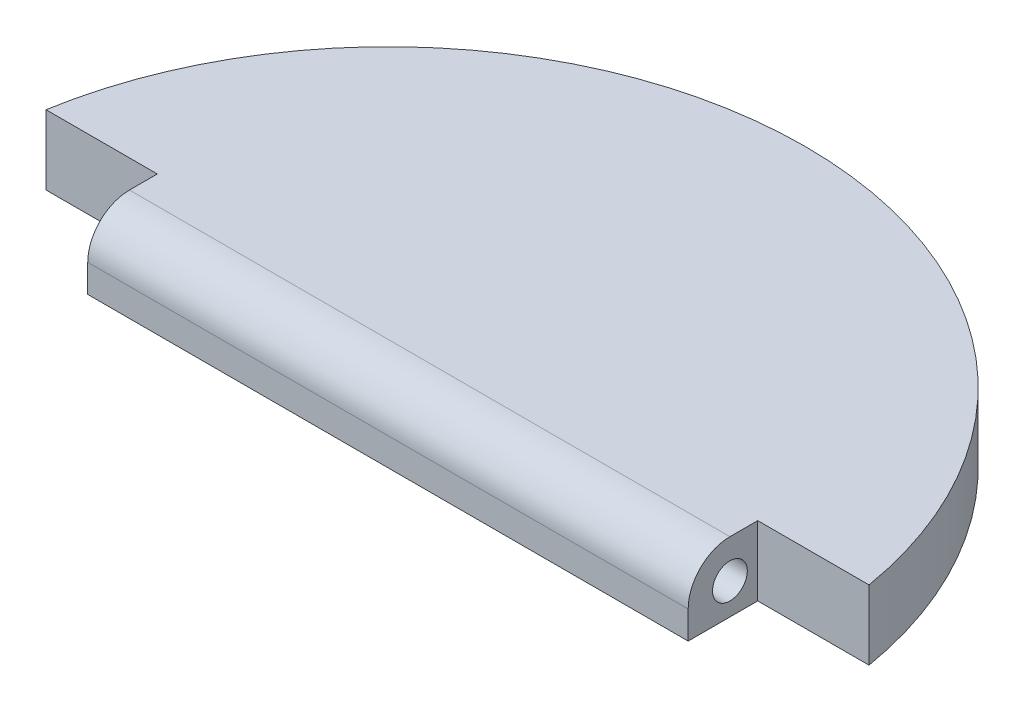
SolidWorks part; units mm, degrees
ref_plane "Front Plane" through (0, 0, 0) normal (0, 0, 1) x (1, 0, 0)
ref_plane "Top Plane" through (0, 0, 0) normal (0, 1, 0) x (1, 0, 0)
ref_plane "Right Plane" through (0, 0, 0) normal (1, 0, 0) x (0, 0, -1)
sketch "Sketch1" plane through (0, 0, 0) normal (0, 1, 0) x (1, 0, 0)
  line L0 (-30, 0) -> (30, 0)
  arc A0 (30, 0) -> (-30, 0) centre (0, 0) ccw
  dimension "D1" = 60
extrude "Boss-Extrude1" add sketch "Sketch1" along normal blind 5
sketch "Sketch5" plane through (0, 5, 0) normal (0, 1, 0) x (1, 0, 0)
  line L0 (-21.5804, 0) -> (-21.5804, 5)
  line L1 (-30, 0) -> (30, 0) construction
  line L2 (-21.5804, 5) -> (-29.5804, 5)
  line L3 (-30, 0) -> (-21.5804, 0)
  line L4 (0, -4.411) -> (0, 4.411) construction
  line L5 (21.5804, 5) -> (29.5804, 5)
  line L6 (21.5804, 0) -> (21.5804, 5)
  line L7 (30, 0) -> (21.5804, 0)
  arc A0 (30, 0) -> (-30, 0) centre (0, 0) ccw construction
  arc A1 (-29.5804, 5) -> (-30, 0) centre (0, 0) ccw
  arc A2 (29.5804, 5) -> (30, 0) centre (0, 0) cw
  dimension "D1" = 8
  dimension "D2" = 5
extrude "Cut-Extrude1" cut sketch "Sketch5" against normal blind 10
fillet "Fillet2" radius 3 1 edges at (0, 5, 0)
sketch "Sketch6" plane through (21.5804, 0, 0) normal (1, 0, 0) x (0, 0, -1)
  line L0 (5, 0) -> (0, 0) construction
  line L1 (0, 0) -> (0, 2) construction
  circle A0 centre (3, 2.25) radius 1.25
  dimension "D1" = 2.5
  dimension "D2" = 2.25
  dimension "D3" = 3
extrude "Cut-Extrude2" cut sketch "Sketch6" against normal blind 3
sketch "Sketch7" plane through (-21.5804, 0, 0) normal (-1, 0, 0) x (0, 0, 1)
  line L0 (0, 0) -> (0, 2) construction
  line L1 (0, 0) -> (-5, 0) construction
  circle A0 centre (-3, 2.25) radius 1.25
  dimension "D1" = 2.5
  dimension "D2" = 3
  dimension "D3" = 2.25
extrude "Cut-Extrude3" cut sketch "Sketch7" against normal blind 3
